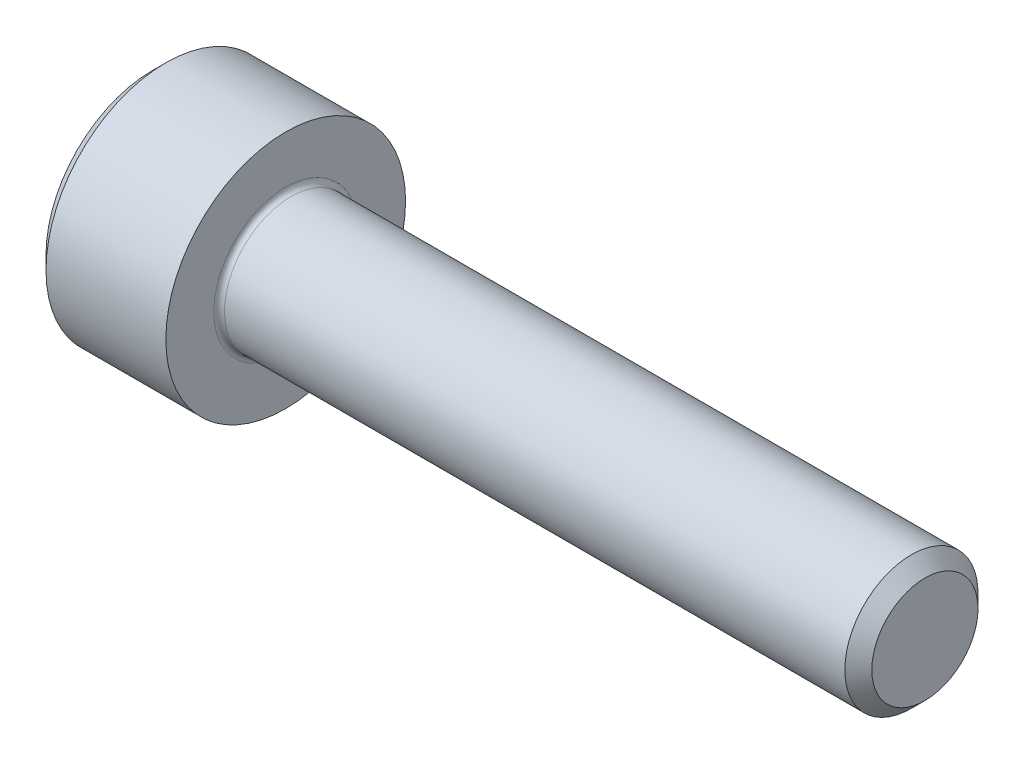
SolidWorks part; units mm, degrees
revolve "Base-Revolve" add sketch "BodySke"
sketch "BodySke" plane through (0, 0, 0) normal (0, 0, 1) x (1, 0, 0)
  line L0 (0, 0) -> (0, 2)
  line L1 (0.25, 2.25) -> (2.5, 2.25)
  line L2 (2.5, 2.25) -> (2.5, 1.25)
  line L3 (2.5, 1.25) -> (14.2465, 1.25)
  line L4 (14.5, 0.9965) -> (14.5, 0)
  line L5 (14.5, 0) -> (0, 0)
  line L6 (-31.75, 0) -> (127, 0) construction
  line L7 (0, 2) -> (0.25, 2.25)
  line L8 (14.5, 0.9965) -> (14.2465, 1.25)
  line L9 (0, -2) -> (0.25, -2.25) construction
  line L10 (14.5, -0.9965) -> (14.2465, -1.25) construction
  line L11 (2.95, 9.525) -> (2.95, 3.175) construction
  line L12 (2.5, 9.525) -> (2.5, 3.175) construction
  line L13 (-35.5, 9.525) -> (-35.5, 3.175) construction
  dimension "Diameter" = 2.5
  dimension "Head_ht" = 2.5
  dimension "Length" = 12
  dimension "Body_ch_ang" = 45
  dimension "Head_dia" = 4.5
  dimension "Head_ch_ang" = 45
  dimension "Minor_dia" = 1.993
  dimension "Advance" = 0.45
  dimension "Thread_nom" = 12
  dimension "Thread_length" = 50
  dimension "Head_ch_ht" = 0.25
cosmetic thread "ThreadCosmetic"
fillet "Fillet1" radius 0.1 1 edges at (2.5, 0, 1.25)
ref_plane "Plane1" through (0, 0, 0) normal (0, 0, 1) x (1, 0, 0)
ref_plane "Plane2" through (0, 0, 0) normal (0, 1, 0) x (1, 0, 0)
ref_plane "Plane3" through (0, 0, 0) normal (1, 0, 0) x (0, 0, -1)
sketch "Sketch2" plane through (0, 0, 0) normal (0, 0, 1) x (1, 0, 0)
  line L0 (0, 1.0225) -> (1.1, 1.0225)
  line L1 (1.1, 1.0225) -> (1.6903, 0)
  line L2 (-31.75, 0) -> (127, 0) construction
  line L3 (1.6903, 0) -> (0, 0)
  line L4 (0, 0) -> (0, 1.0225)
  line L5 (0, 2) -> (0, -2) construction
  line L6 (0, 0) -> (47.625, 0) construction
  line L7 (2.5, -2.25) -> (2.5, 2.25) construction
  dimension "D1" = 1.0225
  dimension "D2" = 60
revolve "Hex-PreBroach" cut sketch "Sketch2" angle 360 about L6
sketch "Sketch3" plane through (0, 0, 0) normal (-1, 0, 0) x (0, 0.5, 0.866)
  line L0 (0.5903, 1.0225) -> (-0.5903, 1.0225)
  line L1 (-0.5903, 1.0225) -> (-1.1807, 0)
  line L2 (0.5903, 1.0225) -> (1.1807, 0)
  line L3 (0.5903, -1.0225) -> (1.1807, 0)
  line L4 (0.5903, -1.0225) -> (-0.5903, -1.0225)
  line L5 (-0.5903, -1.0225) -> (-1.1807, 0)
  dimension "D1" = 1.0225
  dimension "D2" = 1.0225
  dimension "Hex_size" = 2.045
extrude "Hex" cut sketch "Sketch3" against normal blind 1.1
sketch "Sketch4" plane through (0, 0, 0) normal (-1, 0, 0) x (0, 0, 1)
  line L0 (0, 0) -> (1.2446, 0)
  line L1 (0, 0) -> (6.1484, 3.5498) construction
  line L2 (0, 0) -> (0.6223, 1.0779)
  line L3 (1.0085, 0.2596) -> (1.19, 0.3644)
  line L4 (0.7291, 0.7436) -> (0.9106, 0.8484)
  arc A0 (1.0085, 0.2596) -> (0.7291, 0.7436) centre (0, 0) ccw
  arc A1 (1.2446, 0) -> (1.19, 0.3644) centre (0, 0) ccw
  arc A2 (0.6223, 1.0779) -> (0.9106, 0.8484) centre (0, 0) cw
  dimension "D1" = 30
  dimension "D2" = 60
  dimension "Spline_p_dim" = 0.5588
  dimension "D3" = 0.2794
extrude "Spline" [suppressed] cut sketch "Sketch4" against normal blind 1.1
pattern_circular "CirPattern1" [suppressed] count 6 every 60
sketch "Sketch5" plane through (0, 0, 0) normal (0, 0, 1) x (1, 0, 0)
  line L0 (-31.75, 0) -> (127, 0) construction
  line L2 (0, 2) -> (0, -2) construction
  circle A0 centre (0.1, 0) radius 0.005
  dimension "Drilled_hole_dia" = 0.01
  dimension "Drilled_hole_loc" = 0.1
extrude "Hole" [suppressed] cut sketch "Sketch5" against normal through all and the other way through all
pattern_circular "Drilled-4" [suppressed] count 2 every 60
pattern_circular "Drilled-6" [suppressed] count 3 every 60
sketch "ThdSchSke" plane through (0, 0, 0) normal (0, 0, 1) x (1, 0, 0)
  line L0 (2.95, -0.9965) -> (2.7725, -1.25)
  line L1 (2.95, -0.9965) -> (3.1275, -1.25)
  line L2 (3.1275, -1.25) -> (3.1275, -1.5625)
  line L3 (-3.175, 0) -> (5.1513, 0) construction
  line L5 (3.1275, -1.5625) -> (2.7725, -1.5625)
  line L6 (2.7725, -1.5625) -> (2.7725, -1.25)
  line L7 (0, 2) -> (0, -2) construction
  dimension "Thread_minor" = 1.993
  dimension "Diameter" = 2.5
  dimension "Start" = 2.95
revolve "ThreadSchematic" [suppressed] cut sketch "ThdSchSke" angle 360 about L3
pattern_linear "ThdSchPat" [suppressed]
equation "\"D2@Sketch3\" = \"Hex_size@Sketch3\" / 2"
equation "\"D1@Sketch3\" = \"Hex_size@Sketch3\" / 2"
equation "\"D1@Sketch2\" = \"Hex_size@Sketch3\" / 2"
equation "\"D3@Sketch4\" = \"Spline_p_dim@Sketch4\" / 2"
equation "\"Thread_minor@ThreadCosmetic\"  =  \"Minor_dia@BodySke\""
equation "\"D2@CirPattern1\" = 360 / \"Num_teeth@CirPattern1\""
equation "\"Wall_thickness@Sketch2\" = \"Head_ht@BodySke\" - \"Key_eng@Hex\""
equation "\"Thread_length@ThreadCosmetic\" = ((sgn( (\"Length@BodySke\" - \"Advance@BodySke\" ) - \"Thread_nom@BodySke\" )-1)*( (\"Length@BodySke\" - \"Advance@BodySke\" ) - \"Thread_nom@BodySke\" ))/-2+ \"Thread_nom@BodySke\""
equation "\"Thread_minor@ThdSchSke\" = \"Minor_dia@BodySke\""
equation "\"Diameter@ThdSchSke\" = \"Diameter@BodySke\""
equation "\"Overcut@ThdSchSke\" = \"Diameter@BodySke\" * 1.25"
equation "\"Start@ThdSchSke\" = \"Head_ht@BodySke\" + \"Length@BodySke\" - \"Thread_length@ThreadCosmetic\"  '---Non-countersunk---"
equation "\"Num_threads@ThdSchPat\" = int( \"Thread_length@ThreadCosmetic\" / \"Advance@BodySke\" + 0.999 )  + 1"
equation "\"Advance@ThdSchPat\" = \"Thread_length@ThreadCosmetic\" /  (\"Num_threads@ThdSchPat\" - 1) 'relax it"
equation "\"Num_threads@ThdSchPat\" = \"Num_threads@ThdSchPat\" - sgn( \"Num_threads@ThdSchPat\" - 1) '---chamfered tips only---"
